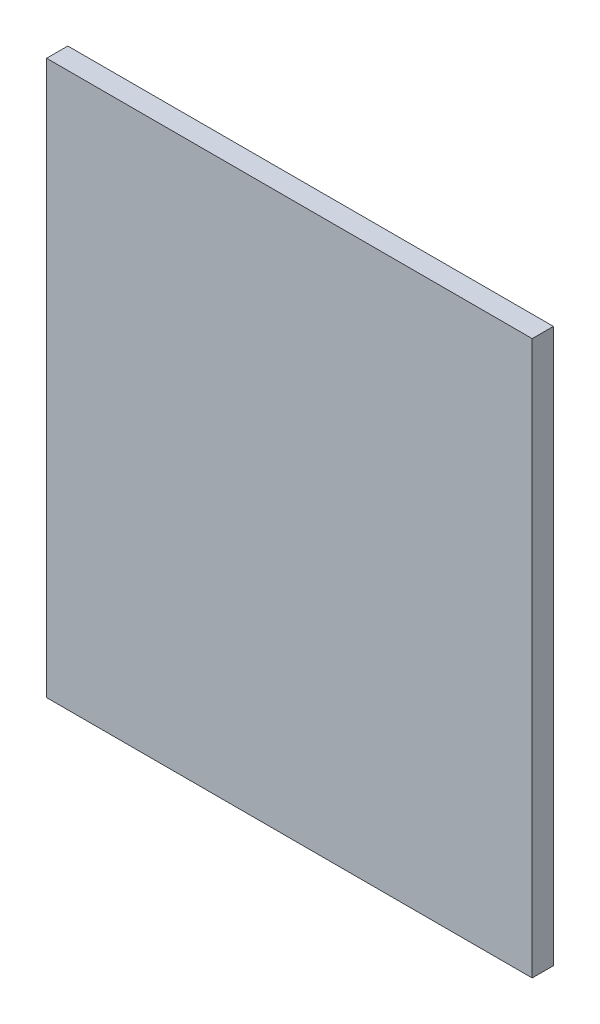
SolidWorks part; units mm, degrees
ref_plane "Front Plane" through (0, 0, 0) normal (0, 0, 1) x (1, 0, 0)
ref_plane "Top Plane" through (0, 0, 0) normal (0, 1, 0) x (1, 0, 0)
ref_plane "Right Plane" through (0, 0, 0) normal (1, 0, 0) x (0, 0, -1)
sketch "Sketch2" plane through (0, 0, 0) normal (0, 1, 0) x (1, 0, 0)
  line L1 (-50.382, 13.3131) -> (-28.632, 13.3131)
  line L2 (-50.382, 13.3131) -> (-50.382, 12.3631)
  line L3 (-50.382, 12.3631) -> (-28.632, 12.3631)
  line L4 (-28.632, 13.3131) -> (-28.632, 12.3631)
extrude "Boss-Extrude1" add sketch "Sketch2" along normal blind 24.8
